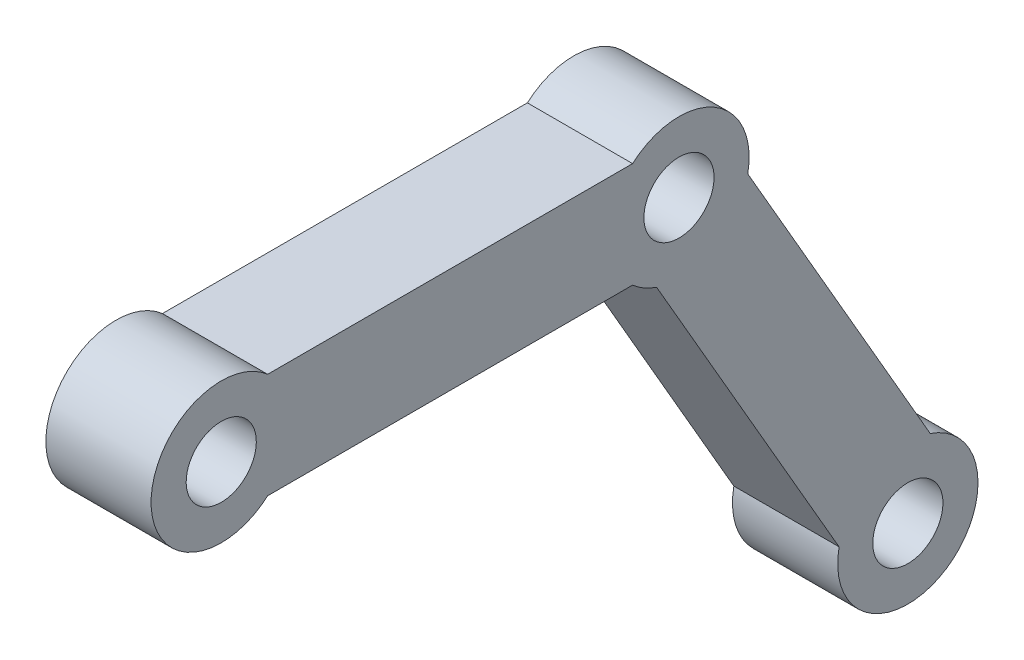
SolidWorks part; units mm, degrees
ref_plane "Front Plane" through (0, 0, 0) normal (0, 0, 1) x (1, 0, 0)
ref_plane "Top Plane" through (0, 0, 0) normal (0, 1, 0) x (1, 0, 0)
ref_plane "Right Plane" through (0, 0, 0) normal (1, 0, 0) x (0, 0, -1)
sketch "Sketch1" plane through (0, 0, 0) normal (1, 0, 0) x (0, 0, -1)
  line L0 (0, 0) -> (0, -81.2) construction
  line L1 (0, 0) -> (-130.5, 0)
  line L2 (0, 0) -> (65.25, -113.0163)
  dimension "D1" = 130.5
  dimension "D2" = 130.5
  dimension "D3" = 120
ref_plane "Plane1" through (0, 0, 130.5) normal (0, 0, 1) x (1, 0, 0)
sketch "Sketch2" plane through (0, 0, 130.5) normal (0, 0, 1) x (1, 0, 0)
  line L0 (12.5, 12.5) -> (12.5, -12.5)
  line L1 (-15, 15) -> (15, 15)
  line L2 (-15, 15) -> (-15, -15)
  line L3 (-15, -15) -> (15, -15)
  line L4 (15, 15) -> (15, -15)
  line L5 (-15, 15) -> (15, -15) construction
  line L6 (-15, -15) -> (15, 15) construction
  line L7 (-12.5, -12.5) -> (12.5, -12.5)
  line L8 (-12.5, 12.5) -> (-12.5, -12.5)
  line L9 (-12.5, 12.5) -> (12.5, 12.5)
  point P0 (0, 0)
  dimension "D1" = 30
  dimension "D2" = 30
  dimension "D3" = 2.5
sweep "Sweep1" add profiles "Sketch2" path "Sketch1"
sketch "Sketch3" plane through (15, 0, 0) normal (1, 0, 0) x (0, 0, -1)
  line L0 (52.2596, -120.5163) -> (78.2404, -105.5163) construction
  line L1 (-130.5, 16.5) -> (-130.5, -16.5) construction
  circle A0 centre (0, 0) radius 20
  circle A1 centre (65.25, -113.0163) radius 20
  circle A2 centre (-130.5, 0) radius 20
extrude "Boss-Extrude2" add sketch "Sketch3" against normal blind 30
sketch "Sketch4" plane through (15, 0, 0) normal (1, 0, 0) x (0, 0, -1)
  circle A0 centre (-130.5, 0) radius 10
  circle A1 centre (0, 0) radius 10
  circle A2 centre (65.25, -113.0163) radius 10
extrude "Cut-Extrude1" cut sketch "Sketch4" against normal blind 30
